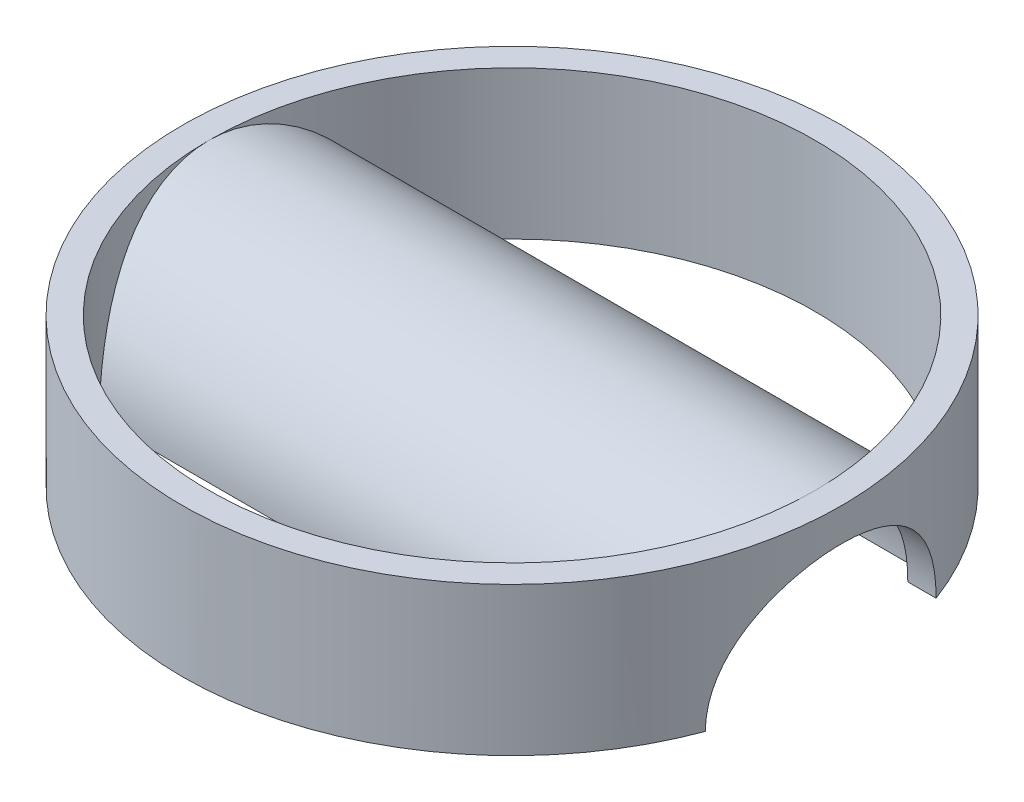
SolidWorks part; units mm, degrees
ref_plane "Front Plane" through (0, 0, 0) normal (0, 0, 1) x (1, 0, 0)
ref_plane "Top Plane" through (0, 0, 0) normal (0, 1, 0) x (1, 0, 0)
ref_plane "Right Plane" through (0, 0, 0) normal (1, 0, 0) x (0, 0, -1)
sketch "Sketch3" plane through (0, 0, 0) normal (1, 0, 0) x (0, 0, -1)
  circle A0 centre (0, 0) radius 1.75
extrude "Stir Bar" add sketch "Sketch3" along normal blind 10
sketch "Sketch4" plane through (0, 0, 0) normal (0, 1, 0) x (1, 0, 0)
  line L0 (-0.2543, -2) -> (10.25, -2)
  line L1 (10.25, -2) -> (10.25, 2)
  line L2 (10.25, 2) -> (-0.25, 2)
  line L3 (-0.25, 2) -> (-0.25, -2)
  line L4 (-0.25, -2) -> (-0.2543, -2)
  line L5 (10, 1.75) -> (0, 1.75) construction
  line L6 (0, -1.75) -> (10, -1.75) construction
  line L7 (0, 1.75) -> (0, -1.75) construction
  line L8 (10, -1.75) -> (10, 1.75) construction
  line L9 (-0.25, 2) -> (-0.25, 2.25)
  line L10 (-0.25, 2.25) -> (10.25, 2.25)
  line L11 (10.25, 2.25) -> (10.25, 2)
  line L12 (-0.25, 0) -> (10.25, 0)
  dimension "D1" = 0.25
  dimension "D2" = 10.5043
  dimension "D3" = 0.25
  dimension "D4" = 0.25
  dimension "D5" = 0.25
revolve "Stir Bar Holder" add sketch "Sketch4" angle 180 about L12
sketch "Sketch5" plane through (0, 0, 0) normal (0, -1, 0) x (1, 0, 0)
  line L0 (0, 0) -> (10, 0)
  circle A0 centre (5, 0) radius 5
  circle A1 centre (5, 0) radius 4.6
  line M3 (10.25, 2.25) -> (-0.25, 2.25)
  line M5 (-0.25, 2) -> (10.25, 2)
extrude "Boss-Extrude1" add sketch "Sketch5" against normal through all contours A1 A0 M3 | A1 A0 M3 M5 | A1 A0 L0 M5 | A1 L0 A0 | A1 A0 M5 M3 | A1 L0 A0 M5
sketch "Sketch10" plane through (0, 0, 0) normal (0, -1, 0) x (1, 0, 0)
  circle A0 centre (5, 0) radius 5
  circle A1 centre (5, 0) radius 5.7118
extrude "Cut-Extrude5" cut sketch "Sketch10" against normal through all
sketch "Sketch9" plane through (0, 0, 0) normal (-1, 0, 0) x (0, 0, 1)
  circle A0 centre (0, 0) radius 1.75
extrude "Cut-Extrude6" cut sketch "Sketch9" against normal through all
